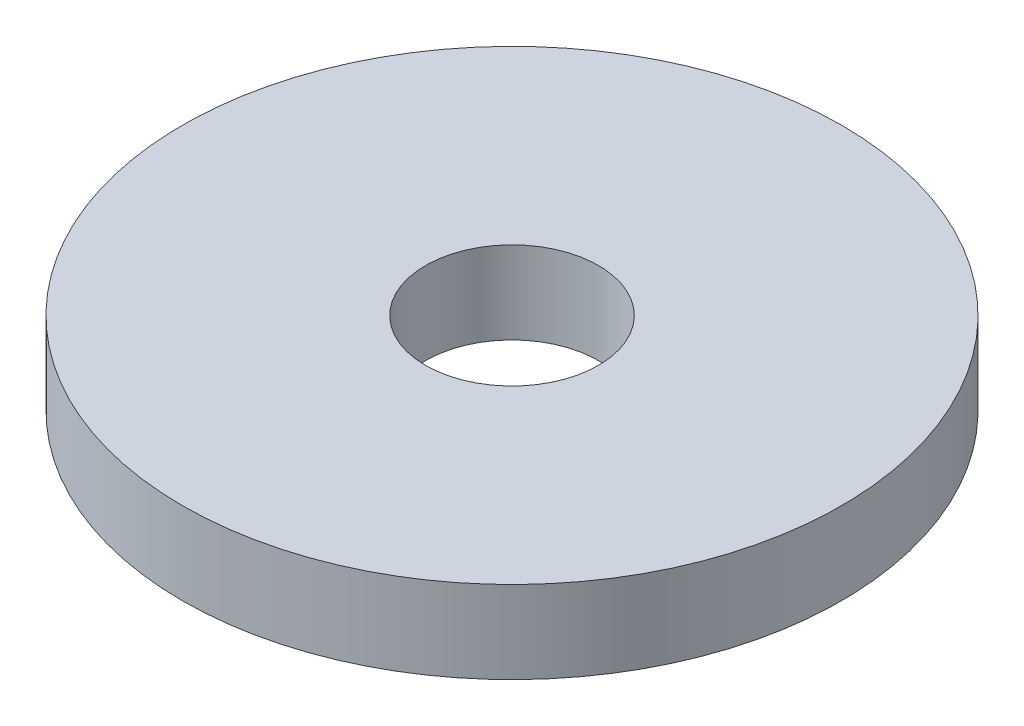
SolidWorks part; units mm, degrees
ref_plane "Front Plane" through (0, 0, 0) normal (0, 0, 1) x (1, 0, 0)
ref_plane "Top Plane" through (0, 0, 0) normal (0, 1, 0) x (1, 0, 0)
ref_plane "Right Plane" through (0, 0, 0) normal (1, 0, 0) x (0, 0, -1)
sketch "Sketch1" plane through (0, 0, 0) normal (0, 1, 0) x (1, 0, 0)
  circle A0 centre (0, 0) radius 8
  circle A1 centre (0, 0) radius 2.1
  dimension "D1" = 16
  dimension "D2" = 4.2
extrude "Boss-Extrude1" add sketch "Sketch1" along normal blind 2
